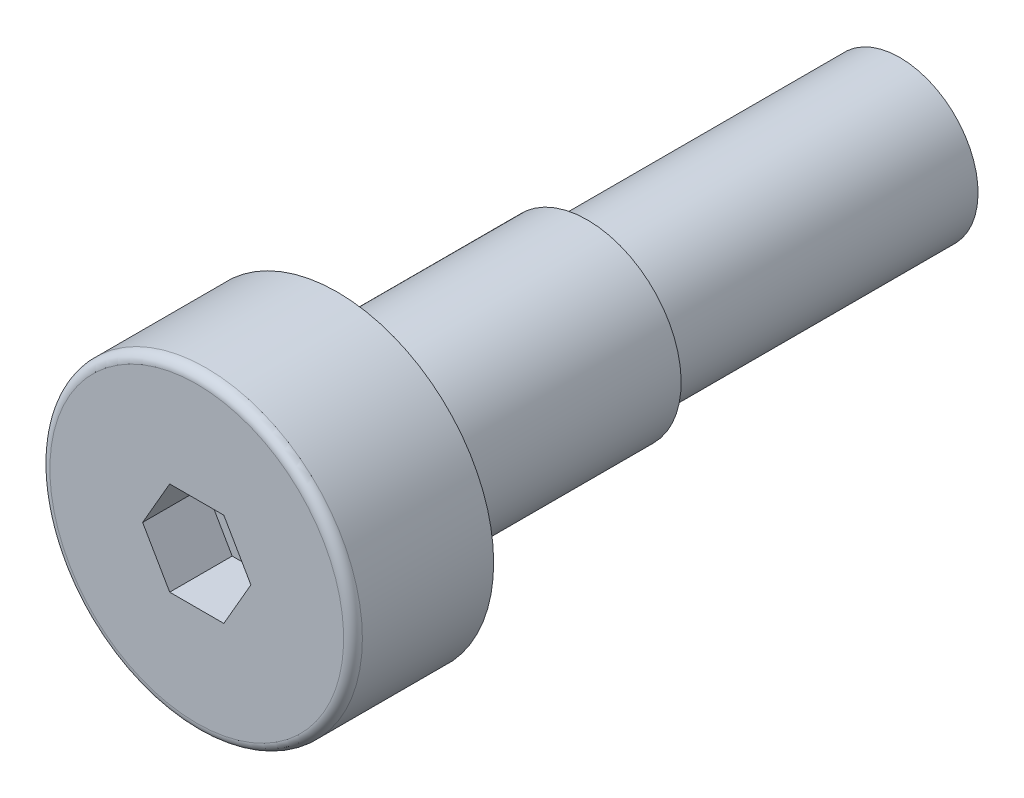
SolidWorks part; units mm, degrees
material "普通碳钢"
ref_plane "前视基准面" through (0, 0, 0) normal (0, 0, 1) x (1, 0, 0)
ref_plane "上视基准面" through (0, 0, 0) normal (0, 1, 0) x (1, 0, 0)
ref_plane "右视基准面" through (0, 0, 0) normal (1, 0, 0) x (0, 0, -1)
sketch "草图1" plane through (0, 0, 0) normal (1, 0, 0) x (0, 0, -1)
  line L0 (0, 0) -> (0, 5)
  line L1 (0, 5) -> (4.5, 5)
  line L2 (4.5, 5) -> (4.5, 3)
  line L3 (4.5, 3) -> (12.5, 3)
  line L4 (12.5, 3) -> (12.5, 2.5)
  line L5 (12.5, 2.5) -> (22.5, 2.5)
  line L6 (22.5, 2.5) -> (22.5, 0)
  line L7 (22.5, 0) -> (0, 0) construction
  line L8 (0, 0) -> (22.5, 0)
  dimension "头部直径" = 10
  dimension "头部厚度" = 4.5
  dimension "光杆长度" = 8
  dimension "光杆直径" = 6
  dimension "螺纹直径" = 5
  dimension "螺纹长度" = 10
revolve "旋转1" add sketch "草图1" angle 360 about L7
cosmetic thread "装饰螺纹线1" parameters "D2"=4
sketch "草图2" plane through (0, 0, 0) normal (0, 0, 1) x (1, 0, 0)
  line L1 (0.866, 1.5) -> (-0.866, 1.5)
  line L2 (-0.866, 1.5) -> (-1.7321, 0)
  line L3 (-1.7321, 0) -> (-0.866, -1.5)
  line L4 (-0.866, -1.5) -> (0.866, -1.5)
  line L5 (0.866, -1.5) -> (1.7321, 0)
  line L6 (1.7321, 0) -> (0.866, 1.5)
  circle A0 centre (0, 0) radius 1.5 construction
  dimension "对边长度" = 3
extrude "切除-拉伸1" cut sketch "草图2" against normal blind 2
fillet "圆角1" radius 0.3 1 edges at (0, 5, 0)
